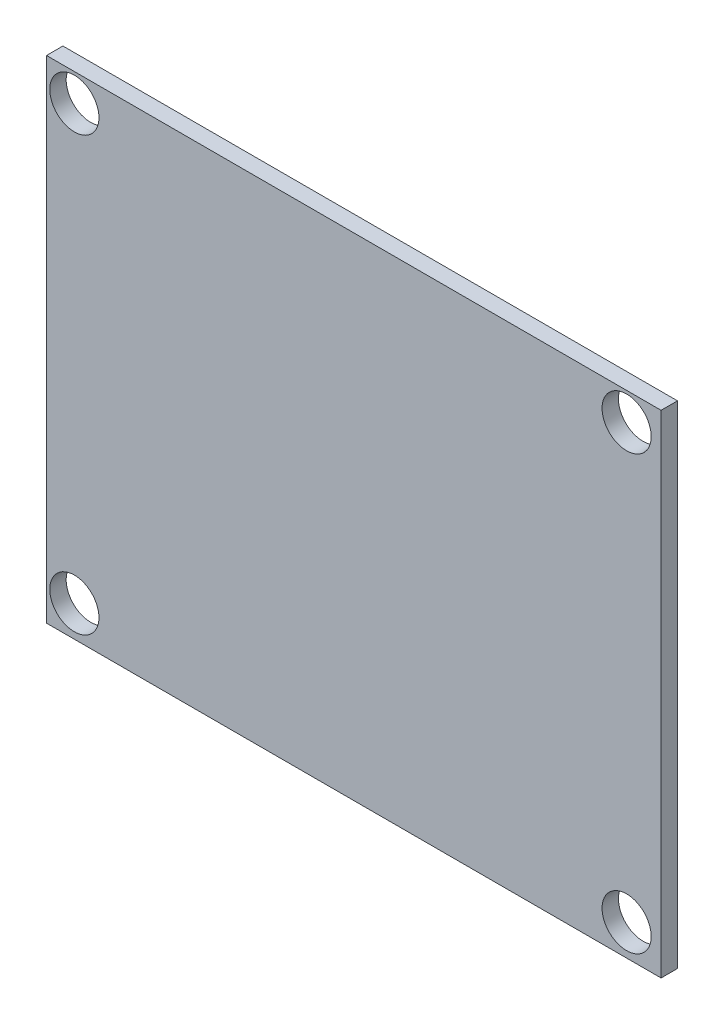
SolidWorks part; units mm, degrees
ref_plane "Plan de face" through (0, 0, 0) normal (0, 0, 1) x (1, 0, 0)
ref_plane "Plan de dessus" through (0, 0, 0) normal (0, 1, 0) x (1, 0, 0)
ref_plane "Plan de droite" through (0, 0, 0) normal (1, 0, 0) x (0, 0, -1)
sketch "Esquisse3" plane through (0, 0, 0) normal (0, 0, 1) x (1, 0, 0)
  line L0 (-17, 13.6) -> (17, 13.6) construction
  line L1 (-37.5, -30) -> (37.5, -30)
  line L2 (-37.5, -30) -> (-37.5, 30)
  line L3 (-37.5, 30) -> (37.5, 30)
  line L4 (37.5, -30) -> (37.5, 30)
  line L5 (-37.5, -30) -> (37.5, 30) construction
  line L6 (-37.5, 30) -> (37.5, -30) construction
  line L7 (17, 13.6) -> (6.0484, -7.4) construction
  circle A0 centre (-17, 13.6) radius 6
  circle A1 centre (17, 13.6) radius 6
  circle A2 centre (6.0484, -7.4) radius 2
  point P0 (0, 0)
  dimension "D4" = 12
  dimension "D5" = 12
  dimension "D6" = 4
  dimension "D1" = 75
  dimension "D2" = 60
  dimension "D3" = 34
  dimension "D7" = 21
extrude "Boss.-Extru.4" add sketch "Esquisse3" along normal blind 2 contours L2 L3 L4 L1
sketch "Esquisse8" plane through (0, 0, 0) normal (0, 0, -1) x (-1, 0, 0)
sketch "Esquisse9" plane through (0, 0, 2) normal (0, 0, 1) x (1, 0, 0)
  circle A0 centre (-34.1013, 26.6176) radius 3
  circle A1 centre (33.2923, 26.6176) radius 3
  circle A2 centre (33.2923, -26.2131) radius 3
  circle A3 centre (-34.1013, -26.2131) radius 3
  dimension "D1" = 6
  dimension "D2" = 6
  dimension "D3" = 6
  dimension "D4" = 6
extrude "Enlèv. mat.-Extru.1" cut sketch "Esquisse9" against normal blind 2 contours A3 | A2 | A1 | A0
